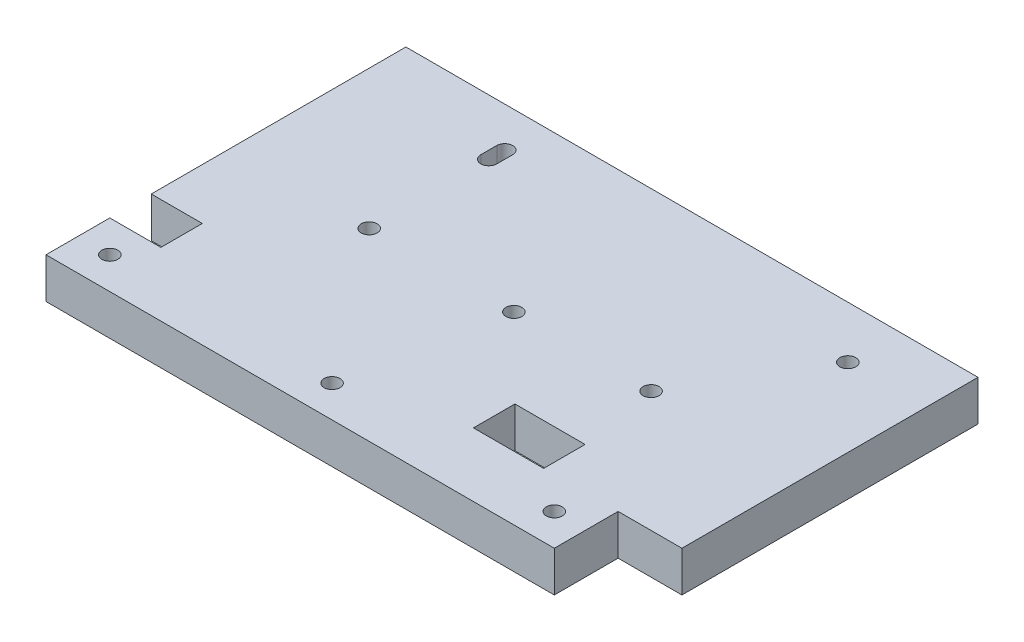
SolidWorks part; units mm, degrees
ref_plane "Front Plane" through (0, 0, 0) normal (0, 0, 1) x (1, 0, 0)
ref_plane "Top Plane" through (0, 0, 0) normal (0, 1, 0) x (1, 0, 0)
ref_plane "Right Plane" through (0, 0, 0) normal (1, 0, 0) x (0, 0, -1)
sketch "Sketch1" plane through (0, 0, 0) normal (0, 1, 0) x (1, 0, 0)
  line L0 (0, 0) -> (159.35, 0)
  line L1 (159.35, 0) -> (159.35, 20)
  line L2 (159.35, 20) -> (179.35, 20)
  line L3 (0, 0) -> (0, 20)
  line L4 (0, 20) -> (16, 20)
  line L5 (16, 20) -> (16, 33)
  line L6 (16, 33) -> (0, 33)
  line L7 (0, 33) -> (0, 112.82)
  line L8 (0, 112.82) -> (179.35, 112.82)
  line L9 (179.35, 112.82) -> (179.35, 20)
  line L10 (43.4872, 95.32) -> (43.4872, 100.32) construction
  line L11 (40.9872, 95.32) -> (40.9872, 100.32)
  line L12 (45.9872, 95.32) -> (45.9872, 100.32)
  line L13 (-18.1986, 55.32) -> (198.6617, 55.32) construction
  line L14 (21, 53.32) -> (154.35, 53.32) construction
  line L15 (21, 53.32) -> (21, 14.58) construction
  line L16 (21, 14.58) -> (154.35, 14.58) construction
  line L17 (154.35, 53.32) -> (154.35, 14.58) construction
  line L18 (157.35, 123.121) -> (157.35, -24.9321) construction
  line L19 (189.217, 47.0044) -> (142.2043, 74.9395) construction
  line L20 (142.0793, 75.0137) -> (144.6335, 79.3121) construction
  line L21 (146.3144, 78.3133) -> (90.8302, 111.2821) construction
  line L22 (0, 10) -> (10, 10) construction
  line L23 (10, 10) -> (10, 0) construction
  line L24 (149.35, 10) -> (159.35, 10) construction
  line L25 (10, 10) -> (149.35, 10) construction
  line L27 (114, 33) -> (136, 33)
  line L28 (114, 33) -> (114, 20)
  line L29 (114, 20) -> (136, 20)
  line L30 (136, 33) -> (136, 20)
  circle A0 centre (43.4872, 57.82) radius 2.5
  circle A1 centre (88.8628, 57.82) radius 2.5
  circle A2 centre (131.8628, 57.82) radius 2.5
  circle A3 centre (154.85, 96.5058) radius 2.5
  arc A4 (40.9872, 95.32) -> (45.9872, 95.32) centre (43.4872, 95.32) ccw
  arc A5 (45.9872, 100.32) -> (40.9872, 100.32) centre (43.4872, 100.32) ccw
  circle A6 centre (43.4872, 57.82) radius 20 construction
  circle A7 centre (88.8628, 57.82) radius 20 construction
  circle A8 centre (131.8628, 57.82) radius 20 construction
  circle A9 centre (154.85, 96.5058) radius 20 construction
  circle A10 centre (43.4872, 97.82) radius 20 construction
  circle A11 centre (10, 10) radius 2.5
  circle A12 centre (79.675, 10) radius 2.5
  circle A13 centre (149.35, 10) radius 2.5
  point P21 (43.4872, 97.82)
  point P46 (111.8628, 57.82)
  point P47 (151.35, 53.32)
  point P48 (24, 53.32)
  point P49 (108.8628, 57.82)
  point P50 (43.4872, 102.82)
  dimension "D3" = 5
  dimension "D4" = 40
  dimension "D19" = 5
  dimension "D1" = 20
  dimension "D2" = 13
  dimension "D5" = 133.35
  dimension "D6" = 38.74
  dimension "D7" = 20.32
  dimension "D8" = 5
  dimension "D9" = 16
  dimension "D10" = 5
  dimension "D11" = 2
  dimension "D12" = 2
  dimension "D13" = 5
  dimension "D14" = 3
  dimension "D15" = 3
  dimension "D16" = 3
  dimension "D17" = 5
  dimension "D18" = 10
  dimension "D20" = 22
  dimension "D21" = 98
extrude "Boss-Extrude1" add sketch "Sketch1" along normal mid plane 12.7
